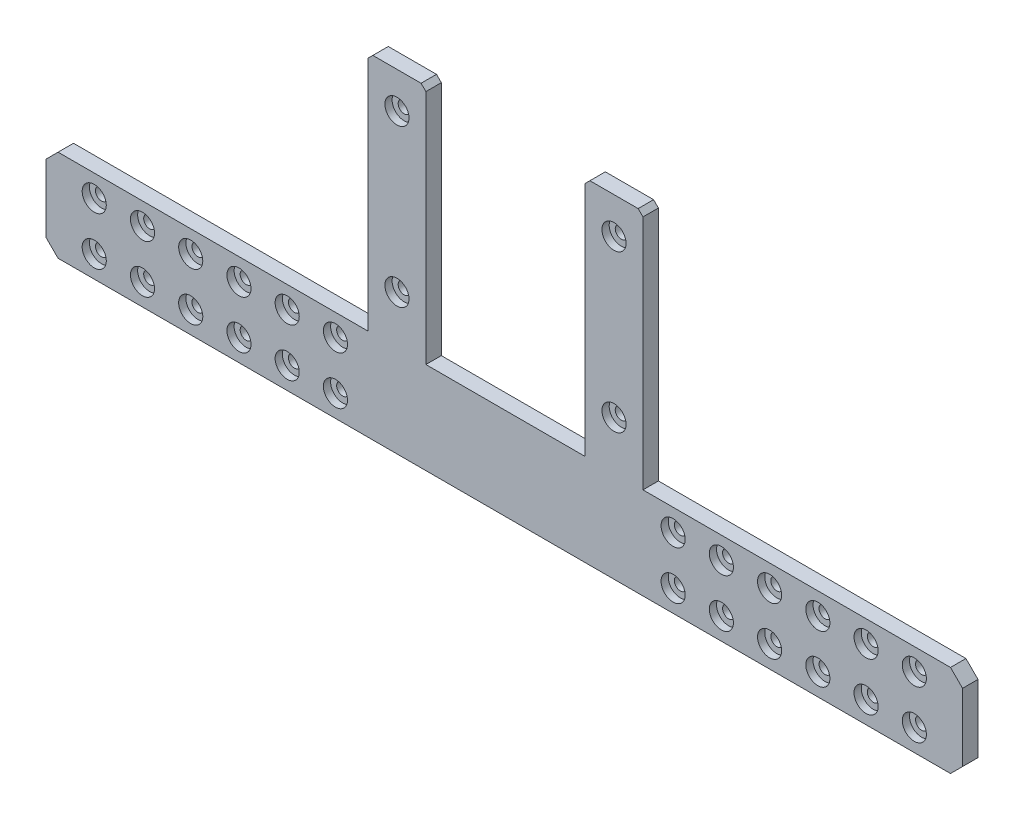
SolidWorks part; units mm, degrees
material "7075-T6, Plate (SS)"
ref_plane "Front Plane" through (0, 0, 0) normal (0, 0, 1) x (1, 0, 0)
ref_plane "Top Plane" through (0, 0, 0) normal (0, 1, 0) x (1, 0, 0)
ref_plane "Right Plane" through (0, 0, 0) normal (1, 0, 0) x (0, 0, -1)
sketch "Sketch1" plane through (0, 0, 0) normal (0, 0, 1) x (1, 0, 0)
  line L0 (0, 0) -> (0, 157.9207) construction
  line L1 (190, -19.05) -> (-190, -19.05)
  line L2 (190, -19.05) -> (190, 19.05)
  line L3 (190, 19.05) -> (57.5, 19.05)
  line L4 (-190, -19.05) -> (-190, 19.05)
  line L5 (190, -19.05) -> (-190, 19.05) construction
  line L6 (190, 19.05) -> (-190, -19.05) construction
  line L8 (-56.5, 19.05) -> (-56.5, 119.05)
  line L9 (-56.5, 119.05) -> (-32.5, 119.05)
  line L10 (-32.5, 19.05) -> (-32.5, 119.05)
  line L11 (-56.5, 19.05) -> (-32.5, 119.05) construction
  line L12 (-56.5, 119.05) -> (-32.5, 19.05) construction
  line L14 (33.5, 19.05) -> (33.5, 119.05)
  line L15 (33.5, 119.05) -> (57.5, 119.05)
  line L16 (57.5, 19.05) -> (57.5, 119.05)
  line L17 (33.5, 19.05) -> (57.5, 119.05) construction
  line L18 (33.5, 119.05) -> (57.5, 19.05) construction
  line L19 (-56.5, 19.05) -> (-190, 19.05)
  line L20 (33.5, 19.05) -> (-32.5, 19.05)
  line L21 (-190, 0) -> (190, 0) construction
  line L22 (-44.5, 119.05) -> (-44.5, 104.05) construction
  line L23 (45.5, 119.05) -> (45.5, 104.05) construction
  circle A0 centre (-70, 10) radius 2.5
  circle A1 centre (-90, 10) radius 2.5
  circle A2 centre (-110, 10) radius 2.5
  circle A3 centre (-130, 10) radius 2.5
  circle A4 centre (-150, 10) radius 2.5
  circle A5 centre (-170, 10) radius 2.5
  circle A6 centre (-70, -10) radius 2.5
  circle A7 centre (-90, -10) radius 2.5
  circle A8 centre (-110, -10) radius 2.5
  circle A9 centre (-130, -10) radius 2.5
  circle A10 centre (-150, -10) radius 2.5
  circle A11 centre (-170, -10) radius 2.5
  circle A12 centre (170, -10) radius 2.5
  circle A13 centre (150, -10) radius 2.5
  circle A14 centre (130, -10) radius 2.5
  circle A15 centre (110, -10) radius 2.5
  circle A16 centre (90, -10) radius 2.5
  circle A17 centre (70, -10) radius 2.5
  circle A18 centre (70, 10) radius 2.5
  circle A19 centre (90, 10) radius 2.5
  circle A20 centre (110, 10) radius 2.5
  circle A21 centre (130, 10) radius 2.5
  circle A22 centre (150, 10) radius 2.5
  circle A23 centre (170, 10) radius 2.5
  circle A24 centre (-44.5, 39.05) radius 2.5
  circle A25 centre (-44.5, 104.05) radius 2.5
  circle A26 centre (45.5, 104.05) radius 2.5
  circle A27 centre (45.5, 39.05) radius 2.5
  point P0 (0, 0)
  point P10 (-44.5, 69.05)
  point P15 (45.5, 69.05)
  dimension "D8" = 5
  dimension "D13" = 5
  dimension "D1" = 38.1
  dimension "D2" = 380
  dimension "D3" = 100
  dimension "D4" = 24
  dimension "D5" = 24
  dimension "D6" = 32.5
  dimension "D7" = 33.5
  dimension "D9" = 10
  dimension "D10" = 70
  dimension "D12" = 20
  dimension "D14" = 20
  dimension "D15" = 65
  dimension "D11" = 6
extrude "Boss-Extrude1" add sketch "Sketch1" along normal blind 6.4
sketch "Sketch2" plane through (0, 0, 6.4) normal (0, 0, 1) x (1, 0, 0)
  line L0 (-190, 0) -> (0, 0) construction
  line L1 (-190, 19.05) -> (-190, -19.05) construction
  line L2 (0, 0) -> (0, 117.613) construction
  circle A0 centre (-170, 10) radius 5
  circle A1 centre (-150, 10) radius 5
  circle A2 centre (-130, 10) radius 5
  circle A3 centre (-110, 10) radius 5
  circle A4 centre (-90, 10) radius 5
  circle A5 centre (-70, 10) radius 5
  circle A6 centre (-70, -10) radius 5
  circle A7 centre (-90, -10) radius 5
  circle A8 centre (-110, -10) radius 5
  circle A9 centre (-130, -10) radius 5
  circle A10 centre (-150, -10) radius 5
  circle A11 centre (-170, -10) radius 5
  circle A12 centre (170, -10) radius 5
  circle A13 centre (150, -10) radius 5
  circle A14 centre (130, -10) radius 5
  circle A15 centre (110, -10) radius 5
  circle A16 centre (90, -10) radius 5
  circle A17 centre (70, -10) radius 5
  circle A18 centre (70, 10) radius 5
  circle A19 centre (90, 10) radius 5
  circle A20 centre (110, 10) radius 5
  circle A21 centre (130, 10) radius 5
  circle A22 centre (150, 10) radius 5
  circle A23 centre (170, 10) radius 5
  circle A24 centre (-44.5, 104.05) radius 5
  circle A25 centre (-44.5, 39.05) radius 5
  circle A26 centre (45.5, 39.05) radius 5
  circle A27 centre (45.5, 104.05) radius 5
  dimension "D1" = 10
  dimension "D4" = 10
  dimension "D3" = 20
  dimension "D2" = 6
extrude "Cut-Extrude1" cut sketch "Sketch2" against normal blind 3
chamfer "Chamfer1" distance 5 angle 45 4 edges at (190, -19.05, 3.2) (190, 19.05, 3.2) (-190, -19.05, 3.2) (-190, 19.05, 3.2)
chamfer "Chamfer2" distance 2 angle 45 4 edges at (57.5, 119.05, 3.2) (33.5, 119.05, 3.2) (-32.5, 119.05, 3.2) (-56.5, 119.05, 3.2)
